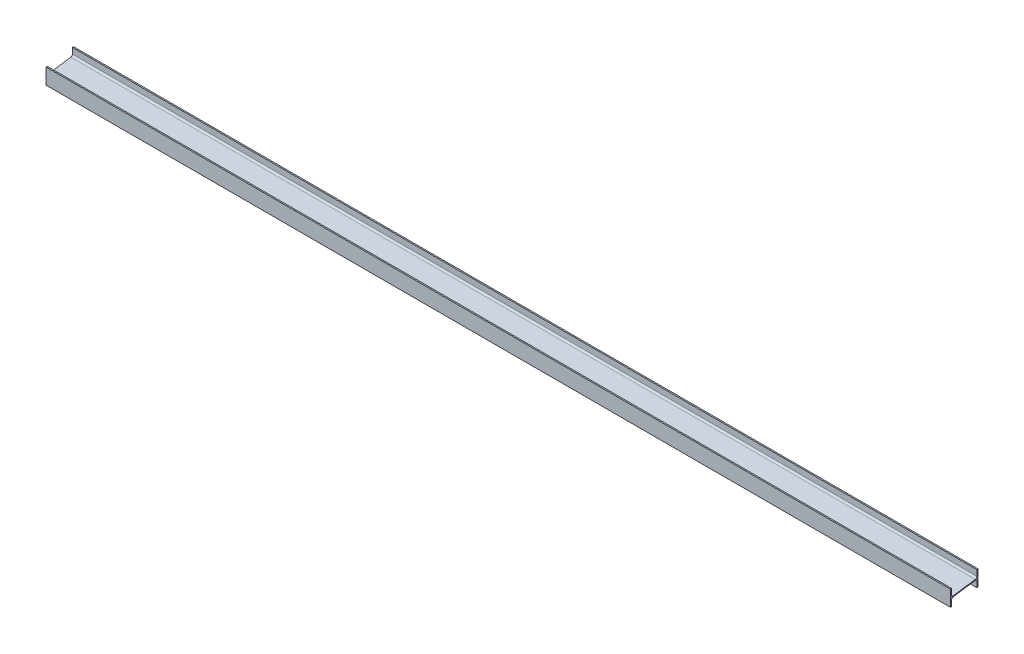
SolidWorks part; units mm, degrees
material "Простая углеродистая сталь"
ref_plane "Спереди" through (0, 0, 0) normal (0, 0, 1) x (1, 0, 0)
ref_plane "Сверху" through (0, 0, 0) normal (0, 1, 0) x (1, 0, 0)
ref_plane "Справа" through (0, 0, 0) normal (1, 0, 0) x (0, 0, -1)
sketch "Эскиз1" plane through (0, 0, 0) normal (0, 0, 1) x (1, 0, 0)
  line L0 (0, 0) -> (5780, 0)
  dimension "D1" = 5780
other "Балочные 20Б1(1)"
ref_plane "Плоскость1" through (0, 0, 0) normal (1, 0, 0) x (0, 1, 0)
sketch "Sketch11" plane through (0, 0, 0) normal (1, 0, 0) x (0, 1, 0)
  line L0 (-126.046, 0) -> (126.046, 0) construction
  line L2 (-13.75, -92) -> (-50, -92)
  line L3 (-13.75, 92) -> (-50, 92)
  line L4 (-2.75, 81) -> (-2.75, -81)
  line L5 (2.75, 81) -> (2.75, -81)
  line L6 (50, -92) -> (50, -100)
  line L7 (-50, -92) -> (-50, -100)
  line L8 (-50, 100) -> (-50, 92)
  line L9 (50, 100) -> (50, 92)
  line L10 (50, -92) -> (13.75, -92)
  line L11 (50, 92) -> (13.75, 92)
  line L12 (50, -100) -> (-50, -100)
  line L13 (0, 126.046) -> (0, -126.046) construction
  line L14 (50, 100) -> (-50, 100)
  arc A0 (13.75, 92) -> (2.75, 81) centre (13.75, 81) ccw
  arc A1 (2.75, -81) -> (13.75, -92) centre (13.75, -81) ccw
  arc A2 (-13.75, -92) -> (-2.75, -81) centre (-13.75, -81) ccw
  arc A3 (-2.75, 81) -> (-13.75, 92) centre (-13.75, 81) ccw
  point P9 (0, 0)
  dimension "R, радиус скругления" = 11
  dimension "В, ширина" = 100
  dimension "H, высота" = 200
  dimension "t, толщина полки" = 8
  dimension "S, толщина стенки" = 5.5
sketch "Эскиз2" plane through (0, -50, 0) normal (0, 1, 0) x (1, 0, 0)
  line L0 (0, 100) -> (25, -100)
  line L2 (25, -100) -> (0, -100)
  line L3 (0, -100) -> (0, 100)
  line L4 (5780, 100) -> (5755, 100)
  line L6 (5755, 100) -> (5780, -100)
  line L7 (5780, -100) -> (5780, 100)
  line L8 (497.0238, -3908.4397) -> (22.2189, -110) construction
  line L9 (5780, 100) -> (0, 100) construction
  line L10 (5780, 92) -> (5780, 100) construction
extrude "Вырез-Вытянуть1" cut sketch "Эскиз2" against normal through all and the other way through all
